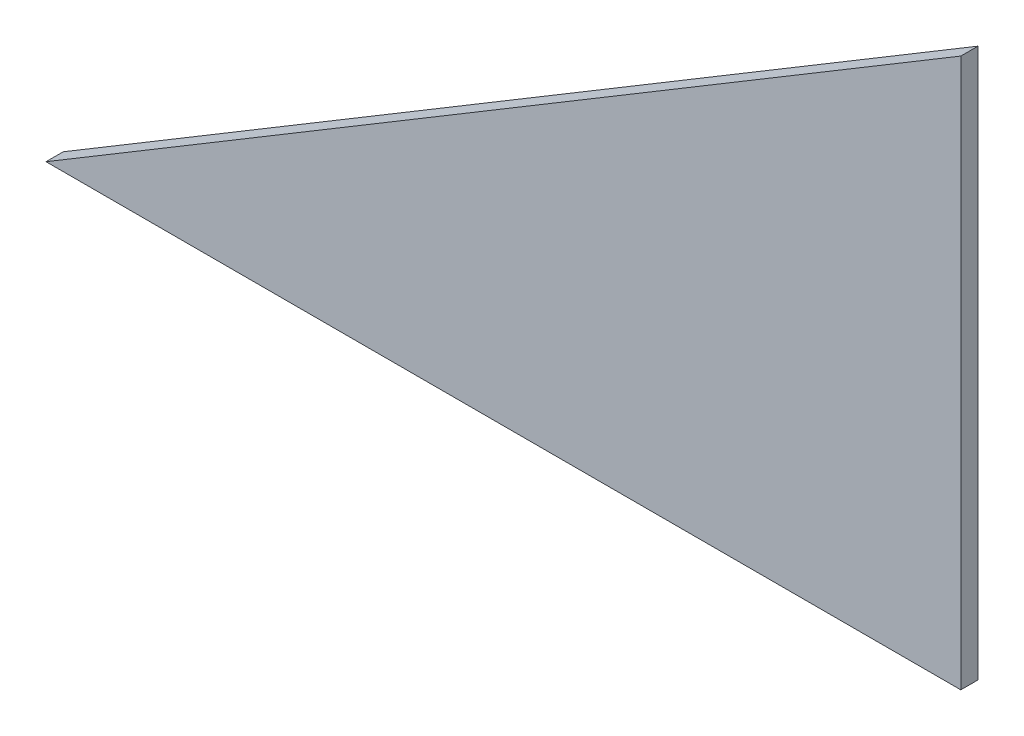
SolidWorks part; units mm, degrees
ref_plane "Front Plane" through (0, 0, 0) normal (0, 0, 1) x (1, 0, 0)
ref_plane "Top Plane" through (0, 0, 0) normal (0, 1, 0) x (1, 0, 0)
ref_plane "Right Plane" through (0, 0, 0) normal (1, 0, 0) x (0, 0, -1)
sketch "Sketch1" plane through (0, 0, 0) normal (0, 0, 1) x (1, 0, 0)
  line L0 (0, 0) -> (-127, 0)
  line L1 (-127, 0) -> (0, 76.2)
  line L2 (0, 76.2) -> (0, 0)
  dimension "D1" = 127
  dimension "D2" = 76.2
extrude "Boss-Extrude1" add sketch "Sketch1" along normal blind 2.3876
